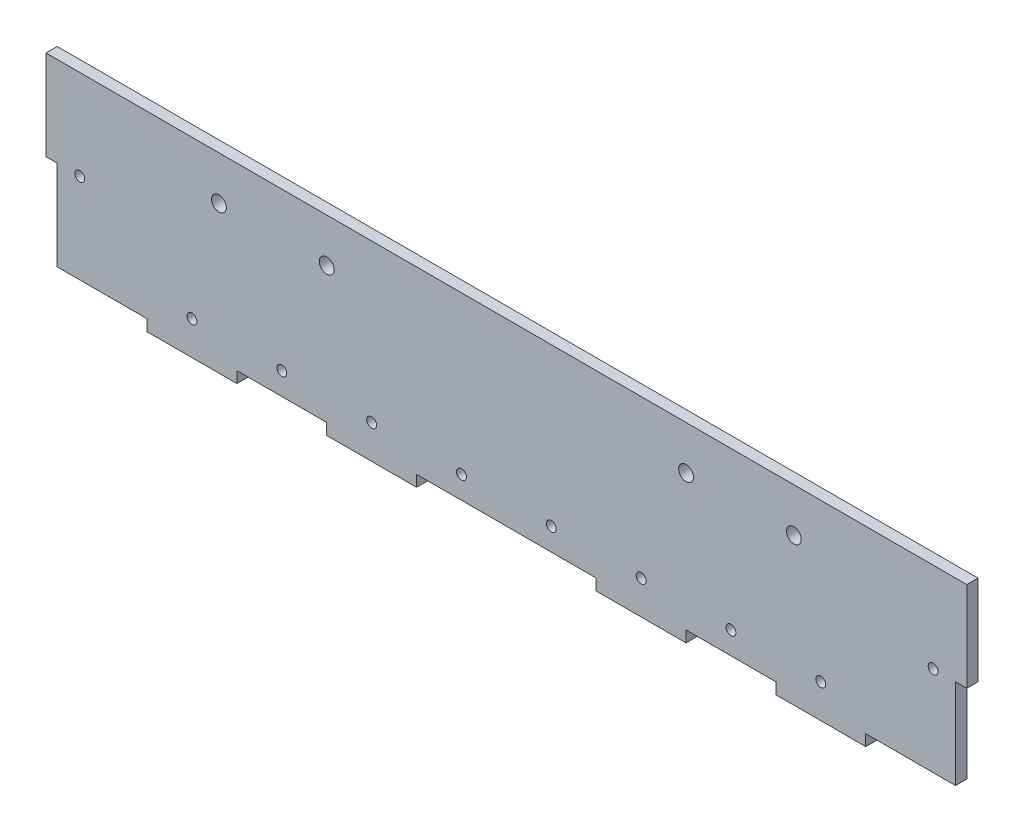
SolidWorks part; units mm, degrees
ref_plane "前视基准面" through (0, 0, 0) normal (0, 0, 1) x (1, 0, 0)
ref_plane "上视基准面" through (0, 0, 0) normal (0, 1, 0) x (1, 0, 0)
ref_plane "右视基准面" through (0, 0, 0) normal (1, 0, 0) x (0, 0, -1)
sketch "草图1" plane through (0, 0, 0) normal (0, 0, 1) x (1, 0, 0)
  line L2 (-200, 150) -> (200, 150)
  line L3 (200, -150) -> (200, -110)
  line L4 (-200, -150) -> (-200, -110)
  line L5 (-200, -150) -> (-160, -150)
  line L6 (-200, -150) -> (-160, -150)
  line L7 (-160, -150) -> (-160, -155)
  line L8 (-160, -155) -> (-120, -155)
  line L9 (-120, -155) -> (-120, -150)
  line L10 (-120, -150) -> (-80, -150)
  line L11 (-80, -150) -> (-80, -155)
  line L12 (-80, -155) -> (-40, -155)
  line L13 (-40, -155) -> (-40, -150)
  line L14 (-40, -150) -> (40, -150)
  line L15 (40, -150) -> (40, -155)
  line L16 (40, -155) -> (80, -155)
  line L17 (80, -155) -> (80, -150)
  line L18 (80, -150) -> (120, -150)
  line L19 (120, -150) -> (120, -155)
  line L20 (120, -155) -> (160, -155)
  line L21 (160, -155) -> (160, -150)
  line L22 (80, -150) -> (120, -150)
  line L23 (-120, -150) -> (-80, -150)
  line L24 (-40, -150) -> (40, -150)
  line L25 (160, -150) -> (200, -150)
  line L26 (-200, 110) -> (-200, 150)
  line L27 (-200, -70) -> (-200, -30)
  line L28 (-205, -30) -> (-205, 30)
  line L29 (-205, 30) -> (-200, 30)
  line L30 (-200, 30) -> (-200, 70)
  line L31 (-200, 70) -> (-205, 70)
  line L32 (-205, 70) -> (-205, 110)
  line L33 (-205, 110) -> (-200, 110)
  line L34 (-205, -30) -> (-200, -30)
  line L35 (-200, -70) -> (-205, -70)
  line L36 (-205, -70) -> (-205, -110)
  line L37 (-205, -110) -> (-200, -110)
  line L38 (-200, 30) -> (-200, 70)
  line L39 (200, 110) -> (200, 150)
  line L40 (205, -70) -> (205, -110)
  line L41 (205, -110) -> (200, -110)
  line L42 (200, -70) -> (205, -70)
  line L43 (205, -30) -> (200, -30)
  line L44 (205, -30) -> (205, 30)
  line L45 (205, 30) -> (200, 30)
  line L46 (200, 70) -> (205, 70)
  line L47 (205, 70) -> (205, 110)
  line L48 (205, 110) -> (200, 110)
  line L49 (200, 30) -> (200, 70)
  line L50 (200, -70) -> (200, -30)
  circle A0 centre (-140, -140) radius 2.2
  circle A1 centre (-100, -140) radius 2.2
  circle A2 centre (-60, -140) radius 2.2
  circle A3 centre (-20, -140) radius 2.2
  circle A4 centre (20, -140) radius 2.2
  circle A5 centre (60, -140) radius 2.2
  circle A6 centre (100, -140) radius 2.2
  circle A7 centre (140, -140) radius 2.2
  circle A8 centre (-190, 110) radius 2.2
  circle A9 centre (-190, 70) radius 2.2
  circle A10 centre (-190, 30) radius 2.2
  circle A11 centre (-190, -30) radius 2.2
  circle A12 centre (-190, -70) radius 2.2
  circle A13 centre (-190, -110) radius 2.2
  circle A14 centre (190, -110) radius 2.2
  circle A15 centre (190, -70) radius 2.2
  circle A16 centre (190, -30) radius 2.2
  circle A17 centre (190, 30) radius 2.2
  circle A18 centre (190, 70) radius 2.2
  circle A19 centre (190, 110) radius 2.2
extrude "凸台-拉伸1" add sketch "草图1" along normal blind 5 contours L42 L50 L43 L44 L45 L49 L46 L47 L48 L39 L2 L26 L33 L32 L31 L30 L29 L28 L34 L27 L35 L36 L37 L4 L5 L7 L8 L9 L10 L11 L12 L13 L14 L15 L16 L17 L18 L19 L20 L21 L25 L3 L41 L40 A18 A16 A14
sketch "草图2" plane through (0, 0, 5) normal (0, 0, 1) x (1, 0, 0)
  line L0 (-205, -70) -> (205, -70)
  line L1 (-205, -70) -> (-205, 156.1054)
  line L2 (205, -70) -> (205, 156.1054)
  line L3 (-205, 156.1054) -> (205, 156.1054)
extrude "切除-拉伸2" cut sketch "草图2" against normal blind 5
sketch "草图4" plane through (0, 0, 5) normal (0, 0, 1) x (1, 0, 0)
  line L0 (-205, -70) -> (205, -70)
  line L1 (-205, -70) -> (-205, -89.4867)
  line L2 (205, -70) -> (205, -89.4867)
  line L3 (-205, -89.4867) -> (205, -89.4867)
extrude "凸台-拉伸3" add sketch "草图4" against normal blind 5
sketch "草图5" plane through (0, 0, 0) normal (0, 0, -1) x (-1, 0, 0)
  circle A0 centre (-80, -89.5) radius 3.3
  circle A1 centre (-128, -89.5) radius 3.3
  circle A2 centre (128, -89.5) radius 3.3
  circle A3 centre (80, -89.5) radius 3.3
extrude "切除-拉伸3" cut sketch "草图5" against normal blind 10
